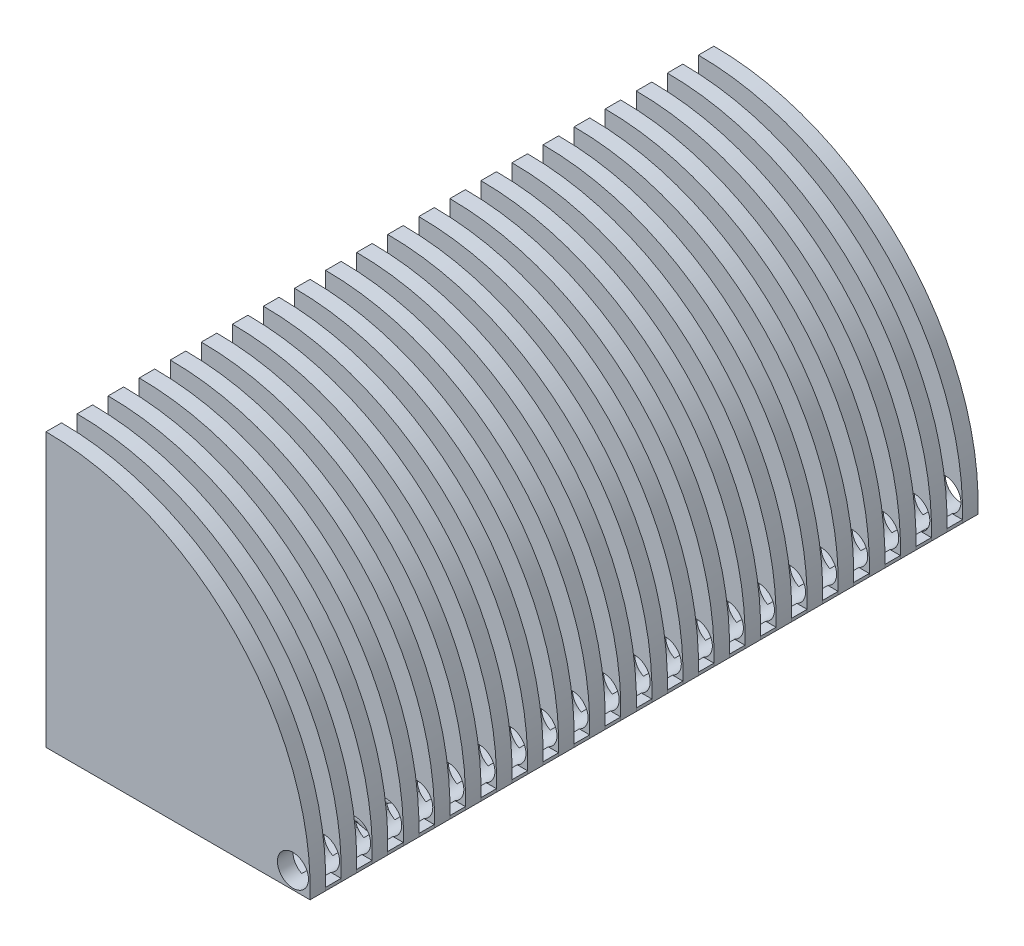
SolidWorks part; units mm, degrees
ref_plane "Front Plane" through (0, 0, 0) normal (0, 0, 1) x (1, 0, 0)
ref_plane "Top Plane" through (0, 0, 0) normal (0, 1, 0) x (1, 0, 0)
ref_plane "Right Plane" through (0, 0, 0) normal (1, 0, 0) x (0, 0, -1)
sketch "Sketch1" plane through (0, 0, 0) normal (0, 0, 1) x (1, 0, 0)
  line L2 (85, 0) -> (0, 0)
  line L3 (0, 0) -> (0, 88)
  arc A1 (0, 88) -> (85, 0) centre (0, 2.9489) cw
  dimension "D1" = 88
  dimension "D2" = 85
extrude "Boss-Extrude1" add sketch "Sketch1" along normal blind 5
pattern_linear "LPattern1" count 22 spacing 10 along (0, 0, -1) of "Boss-Extrude1"
sketch "Sketch2" plane through (0, 0, 5) normal (0, 0, 1) x (1, 0, 0)
  line L0 (0, 0) -> (85, 0) construction
  line L1 (0, -48.4) -> (0, 48.4) construction
  circle A0 centre (79.5, 5.5) radius 5
  dimension "D2" = 10
  dimension "D1" = 5.5
  dimension "D3" = 79.5
sketch "Sketch3" plane through (0, 0, 0) normal (0, 1, 0) x (1, 0, 0)
  line L1 (0, -5) -> (85, -5)
  line L2 (0, -5) -> (0, 210)
  line L3 (0, 210) -> (85, 210)
  line L4 (85, -5) -> (85, 210)
extrude "Boss-Extrude2" add sketch "Sketch3" along normal blind 1
extrude "Cut-Extrude3" cut sketch "Sketch2" against normal through all
